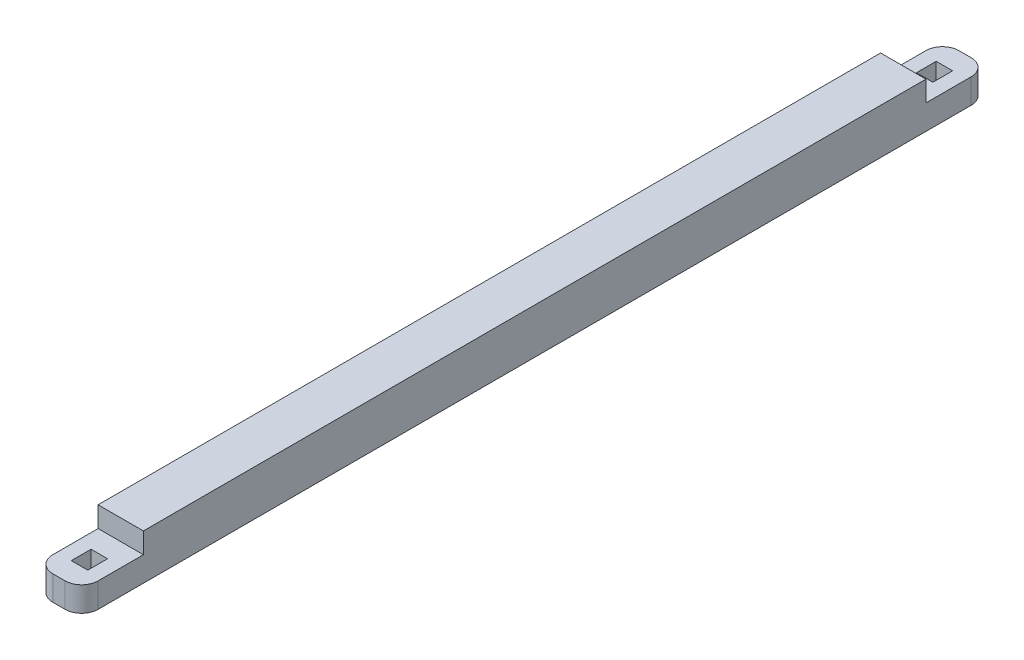
SolidWorks part; units mm, degrees
ref_plane "Front Plane" through (0, 0, 0) normal (0, 0, 1) x (1, 0, 0)
ref_plane "Top Plane" through (0, 0, 0) normal (0, 1, 0) x (1, 0, 0)
ref_plane "Right Plane" through (0, 0, 0) normal (1, 0, 0) x (0, 0, -1)
sketch "Sketch1" plane through (0, 0, 0) normal (0, 0, 1) x (1, 0, 0)
  line L1 (168.7437, 78.7241) -> (203.6687, 78.7241)
  line L2 (168.7437, 78.7241) -> (168.7437, 43.7991)
  line L3 (168.7437, 43.7991) -> (203.6687, 43.7991)
  line L4 (203.6687, 78.7241) -> (203.6687, 43.7991)
  dimension "D1" = 34.925
  dimension "D2" = 34.925
extrude "Boss-Extrude1" add sketch "Sketch1" along normal blind 698.5
sketch "Sketch2" plane through (203.6687, 0, 0) normal (1, 0, 0) x (0, 0, -1)
  line L0 (-349.25, 78.7241) -> (-349.25, 43.7991) construction
  line L1 (-698.5, 78.7241) -> (0, 78.7241) construction
  line L2 (-698.5, 43.7991) -> (0, 43.7991) construction
  line L3 (-47.625, 78.7241) -> (-47.625, 62.8491)
  line L4 (-698.5, 78.7241) -> (-650.875, 78.7241)
  line L5 (-698.5, 78.7241) -> (-698.5, 62.8491)
  line L6 (-698.5, 62.8491) -> (-650.875, 62.8491)
  line L7 (-650.875, 78.7241) -> (-650.875, 62.8491)
  line L8 (0, 62.8491) -> (-47.625, 62.8491)
  line L9 (0, 78.7241) -> (0, 62.8491)
  line L10 (0, 78.7241) -> (-47.625, 78.7241)
  dimension "D1" = 301.625
  dimension "D2" = 15.875
extrude "Cut-Extrude1" cut sketch "Sketch2" against normal blind 127 contours L6 L7 L4 L5
sketch "Sketch3" plane through (0, 62.8491, 0) normal (0, 1, 0) x (1, 0, 0)
  line L0 (168.7437, -675.005) -> (179.8562, -675.005) construction
  line L1 (179.8562, -667.385) -> (192.5562, -667.385)
  line L2 (179.8562, -667.385) -> (179.8562, -682.625)
  line L3 (179.8562, -682.625) -> (192.5562, -682.625)
  line L4 (192.5562, -667.385) -> (192.5562, -682.625)
  line L5 (168.7437, -698.5) -> (168.7437, -650.875) construction
  line L6 (179.8562, -675.005) -> (192.5562, -675.005) construction
  line L7 (192.5562, -675.005) -> (203.6687, -675.005) construction
  line L8 (203.6687, -698.5) -> (203.6687, -650.875) construction
  line L9 (203.6687, -675.005) -> (186.2062, -698.5) construction
  line L10 (168.7437, -698.5) -> (203.6687, -698.5) construction
  line L11 (186.2062, -698.5) -> (186.2062, -682.625) construction
  line L12 (168.7437, -650.875) -> (203.6687, -650.875) construction
  line L13 (203.6687, -349.25) -> (168.7437, -349.25) construction
  line L14 (203.6687, -650.875) -> (203.6687, -47.625) construction
  line L15 (168.7437, -650.875) -> (168.7437, -47.625) construction
  line L16 (179.8562, -31.115) -> (192.5562, -31.115)
  line L17 (192.5562, -31.115) -> (192.5562, -15.875)
  line L18 (179.8562, -15.875) -> (192.5562, -15.875)
  line L19 (179.8562, -31.115) -> (179.8562, -15.875)
  dimension "D1" = 16.51
  dimension "D2" = 12.7
  dimension "D3" = 15.24
extrude "Cut-Extrude2" cut sketch "Sketch3" against normal through all
fillet "Fillet1" radius 12.7 4 edges at (168.7437, 53.3241, 0) (203.6687, 53.3241, 0) (203.6687, 53.3241, 698.5) (168.7437, 53.3241, 698.5)
sketch "Sketch4" plane through (0, 0, 0) normal (0, 0, 1) x (1, 0, 0)
  line L0 (186.2062, 78.7241) -> (186.2062, 43.7991) construction
  line L1 (168.7437, 78.7241) -> (203.6687, 78.7241) construction
  line L2 (181.4437, 43.7991) -> (190.9687, 43.7991) construction
  line L3 (168.7437, 43.7991) -> (168.7437, 62.8491) construction
  line L4 (168.7437, 66.0241) -> (175.0937, 66.0241)
  line L5 (168.7437, 66.0241) -> (168.7437, 59.6741)
  line L6 (168.7437, 59.6741) -> (175.0937, 59.6741)
  line L7 (175.0937, 66.0241) -> (175.0937, 59.6741)
  line L9 (197.3187, 66.0241) -> (197.3187, 59.6741)
  line L10 (203.6687, 59.6741) -> (197.3187, 59.6741)
  line L11 (203.6687, 66.0241) -> (203.6687, 59.6741)
  line L12 (203.6687, 66.0241) -> (197.3187, 66.0241)
  dimension "D1" = 6.35
  dimension "D2" = 12.7
  dimension "D3" = 6.35
extrude "Cut-Extrude3" [suppressed] cut sketch "Sketch4" along normal through all contours L7 L4 L5 L6 | L11 L12 L9 L10
